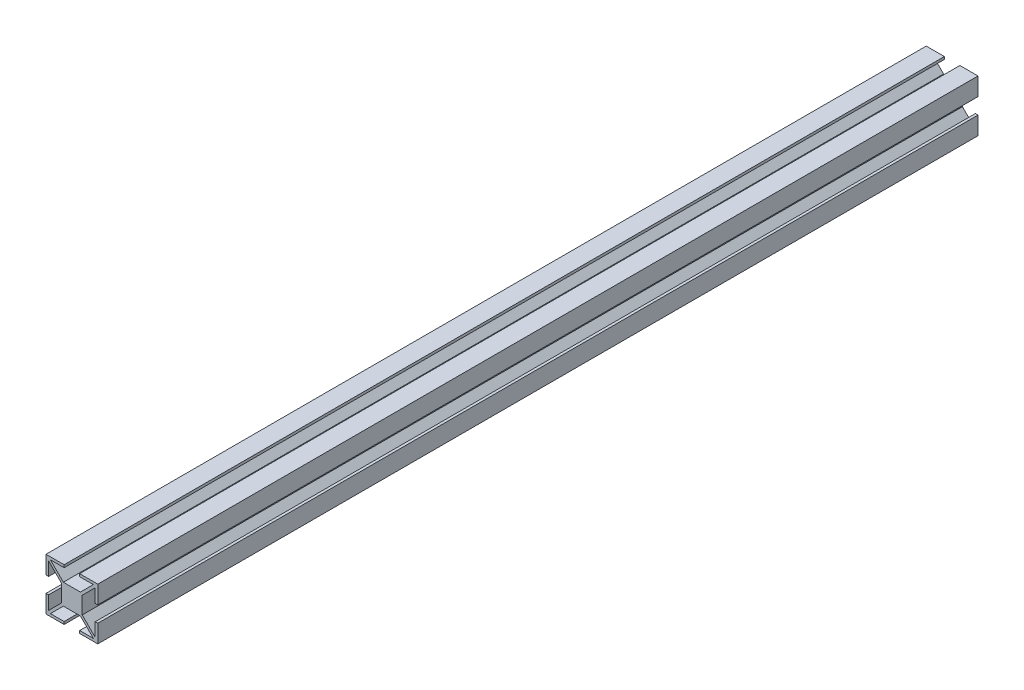
SolidWorks part; units mm, degrees
ref_plane "Front Plane" through (0, 0, 0) normal (0, 0, 1) x (1, 0, 0)
ref_plane "Top Plane" through (0, 0, 0) normal (0, 1, 0) x (1, 0, 0)
ref_plane "Right Plane" through (0, 0, 0) normal (1, 0, 0) x (0, 0, -1)
sketch "Sketch2" plane through (0, 0, 0) normal (0, 0, 1) x (1, 0, 0)
  line L0 (-10, 10) -> (-3, 10)
  line L1 (-3.2929, -4) -> (3.2929, -4)
  line L2 (-4, -3.2929) -> (-4, 3.2929)
  line L3 (-3.2929, 4) -> (3.2929, 4)
  line L4 (4, -3.2929) -> (4, 3.2929)
  line L5 (-4, -4) -> (4, 4) construction
  line L6 (-4, 4) -> (4, -4) construction
  line L7 (-10, -10) -> (10, -10) construction
  line L8 (-10, -10) -> (-10, 10) construction
  line L9 (-10, 10) -> (10, 10) construction
  line L10 (10, -10) -> (10, 10) construction
  line L11 (-10, -10) -> (10, 10) construction
  line L12 (-10, 10) -> (10, -10) construction
  line L13 (-10, 10) -> (-10, 3.074)
  line L14 (0, -11) -> (0, 11) construction
  line L15 (10, 10) -> (10, 3.074)
  line L16 (10, 10) -> (3, 10)
  line L17 (11, 0) -> (-11, 0) construction
  line L18 (10, -10) -> (10, -3.074)
  line L19 (10, -10) -> (3, -10)
  line L20 (-10, -10) -> (-3, -10)
  line L21 (-10, -10) -> (-10, -3.074)
  line L22 (-9, 8.2929) -> (-9, 3.074)
  line L23 (-8.2929, 9) -> (-3, 9)
  line L24 (-3, 10) -> (-3, 9)
  line L25 (-10, 3.074) -> (-9, 3.074)
  line L26 (-3, -10) -> (-3, -9)
  line L27 (-8.2929, -9) -> (-3, -9)
  line L28 (-9, -8.2929) -> (-9, -3.074)
  line L29 (-10, -3.074) -> (-9, -3.074)
  line L30 (10, 3.074) -> (9, 3.074)
  line L31 (9, 8.2929) -> (9, 3.074)
  line L32 (8.2929, 9) -> (3, 9)
  line L33 (3, 10) -> (3, 9)
  line L34 (3, -10) -> (3, -9)
  line L35 (8.2929, -9) -> (3, -9)
  line L36 (9, -8.2929) -> (9, -3.074)
  line L37 (10, -3.074) -> (9, -3.074)
  line L38 (-9, 9) -> (-3, 3) construction
  line L39 (-9, 8.2929) -> (-4, 3.2929)
  line L40 (-8.2929, 9) -> (-3.2929, 4)
  line L41 (-8.6464, 9.3536) -> (-2.6464, 3.3536) construction
  line L42 (-9.3536, 8.6464) -> (-3.3536, 2.6464) construction
  line L43 (-9, 9) -> (-3, 9) construction
  line L44 (-9, 9) -> (-9, 3.074) construction
  line L45 (9, 8.2929) -> (4, 3.2929)
  line L46 (8.2929, 9) -> (3.2929, 4)
  line L47 (9, -8.2929) -> (4, -3.2929)
  line L48 (8.2929, -9) -> (3.2929, -4)
  line L49 (-9, -8.2929) -> (-4, -3.2929)
  line L50 (-8.2929, -9) -> (-3.2929, -4)
  point P0 (0, 0)
  point P6 (0, 0)
  point P26 (-9, 5.6835)
  point P28 (-9, -5.6835)
  dimension "D1" = 8
  dimension "D2" = 8
  dimension "D3" = 20
  dimension "D4" = 20
  dimension "D5" = 1
  dimension "D8" = 45
  dimension "D9" = 6.5858
  dimension "D10" = 6.5858
  dimension "D11" = 1
  dimension "D6" = 0.5
  dimension "D7" = 0.5
extrude "Boss-Extrude1" add sketch "Sketch2" along normal blind 340
